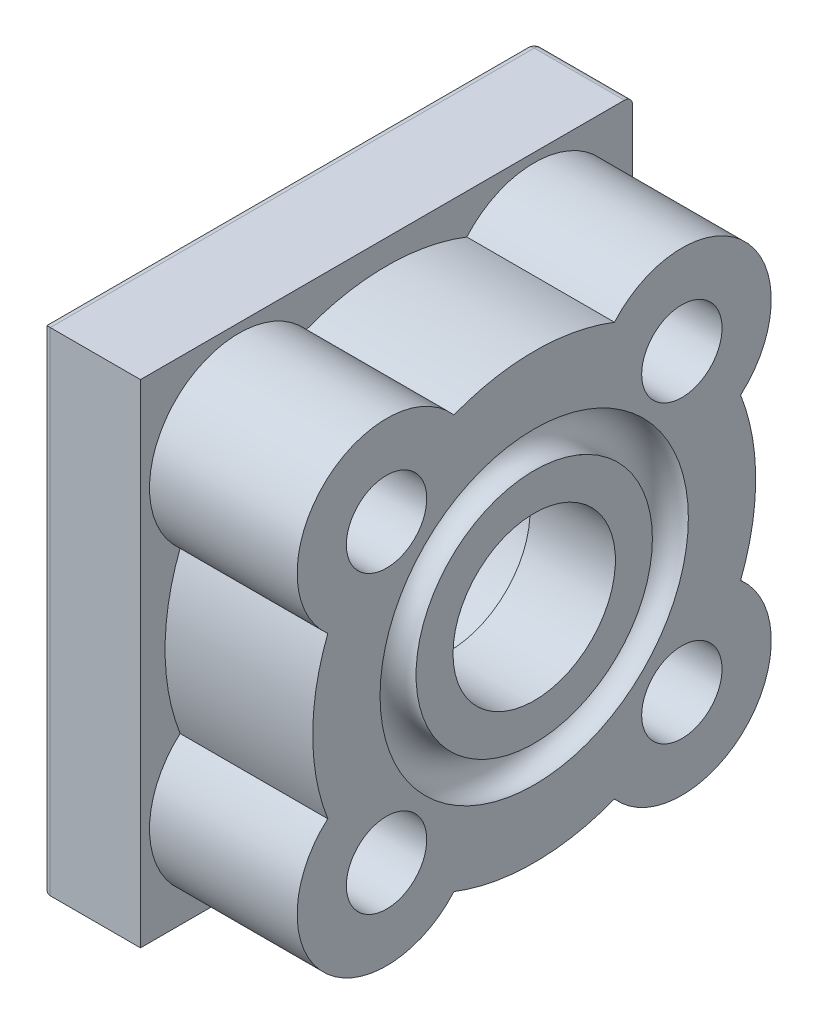
SolidWorks part; units mm, degrees
ref_plane "Front Plane" through (0, 0, 0) normal (0, 0, 1) x (1, 0, 0)
ref_plane "Top Plane" through (0, 0, 0) normal (0, 1, 0) x (1, 0, 0)
ref_plane "Right Plane" through (0, 0, 0) normal (1, 0, 0) x (0, 0, -1)
sketch "Sketch1" plane through (0, 0, 0) normal (1, 0, 0) x (0, 0, -1)
  line L1 (0, 0) -> (30, 0)
  line L2 (0, 0) -> (0, 30)
  line L3 (0, 30) -> (30, 30)
  line L4 (30, 0) -> (30, 30)
  dimension "D1" = 30
  dimension "D2" = 30
extrude "Boss-Extrude1" add sketch "Sketch1" along normal blind 15
sketch "Sketch2" plane through (0, 0, 0) normal (-1, 0, 0) x (0, 0, 1)
  line L0 (-30, 30) -> (0, 30) construction
  line L1 (-30, 0) -> (-30, 30) construction
  line L2 (0, 30) -> (0, 0) construction
  line L3 (0, 0) -> (-30, 0) construction
  circle A0 centre (-24, 24) radius 2.45
  circle A1 centre (-6, 24) radius 2.45
  circle A2 centre (-6, 6) radius 2.45
  circle A3 centre (-24, 6) radius 2.45
  dimension "D2" = 6
  dimension "D3" = 6
  dimension "D5" = 6
  dimension "D6" = 6
  dimension "D7" = 6
  dimension "D8" = 6
  dimension "D9" = 4.9
  dimension "D1" = 6
  dimension "D4" = 6
extrude "Cut-Extrude1" cut sketch "Sketch2" against normal through all
sketch "Sketch3" plane through (0, 0, 0) normal (-1, 0, 0) x (0, 0, 1)
  line L0 (-30, 30) -> (0, 30) construction
  line L1 (-7.6099, 15) -> (-11.305, 21.4)
  line L2 (-11.305, 21.4) -> (-18.695, 21.4)
  line L3 (-18.695, 21.4) -> (-22.3901, 15)
  line L4 (-22.3901, 15) -> (-18.695, 8.6)
  line L5 (-18.695, 8.6) -> (-11.305, 8.6)
  line L6 (-11.305, 8.6) -> (-7.6099, 15)
  line L7 (0, 30) -> (0, 0) construction
  circle A0 centre (-15, 15) radius 6.4 construction
  dimension "D1" = 15
  dimension "D2" = 15
  dimension "D3" = 12.8
extrude "Cut-Extrude2" cut sketch "Sketch3" against normal blind 6.5
sketch "Sketch4" plane through (6.5, 0, 0) normal (-1, 0, 0) x (0, 0, 1)
  line L0 (-11.305, 21.4) -> (-18.695, 21.4) construction
  line L1 (-18.695, 21.4) -> (-22.3901, 15) construction
  circle A0 centre (-15, 15) radius 6.4
  dimension "D1" = 12.8
extrude "Cut-Extrude3" cut sketch "Sketch4" against normal blind 3.3
sketch "Sketch5" plane through (9.8, 0, 0) normal (-1, 0, 0) x (0, 0, 1)
  circle A0 centre (-15, 15) radius 4.95
  dimension "D1" = 9.9
extrude "Cut-Extrude4" cut sketch "Sketch5" against normal through all
ref_plane "Plane1" through (0, 0, -15) normal (0, 0, 1) x (1, 0, 0)
sketch "Sketch6" plane through (0, 0, -15) normal (0, 0, 1) x (1, 0, 0)
  line L0 (9.8, 15) -> (0, 15) construction
  line L1 (9.8, 21.4) -> (9.8, 8.6) construction
  line L2 (15, 30) -> (15, 0) construction
  circle A0 centre (14.4, 23.3) radius 1.25
  dimension "D3" = 8.3
  dimension "D4" = 2.5
  dimension "D5" = 0.6
revolve "Cut-Revolve1" cut sketch "Sketch6" angle 360 about L0
fillet "Fillet1" radius 0.5 6 edges at (7.5, 0, -30) (0, 15, -30) (0, 0, -15) (0, 15, 0) (0, 30, -15) (7.5, 30, -30)
sketch "Sketch7" plane through (0, 0, 0) normal (-1, 0, 0) x (0, 0, 1)
  line L1 (-18.6306, 24) -> (-21.3153, 28.65)
  line L2 (-21.3153, 28.65) -> (-26.6847, 28.65)
  line L3 (-26.6847, 28.65) -> (-29.3694, 24)
  line L4 (-29.3694, 24) -> (-26.6847, 19.35)
  line L5 (-26.6847, 19.35) -> (-21.3153, 19.35)
  line L6 (-21.3153, 19.35) -> (-18.6306, 24)
  line L7 (-0.6306, 24) -> (-3.3153, 28.65)
  line L8 (-3.3153, 28.65) -> (-8.6847, 28.65)
  line L9 (-8.6847, 28.65) -> (-11.3694, 24)
  line L10 (-11.3694, 24) -> (-8.6847, 19.35)
  line L11 (-8.6847, 19.35) -> (-3.3153, 19.35)
  line L12 (-3.3153, 19.35) -> (-0.6306, 24)
  line L13 (-0.6306, 6) -> (-3.3153, 10.65)
  line L14 (-3.3153, 10.65) -> (-8.6847, 10.65)
  line L15 (-8.6847, 10.65) -> (-11.3694, 6)
  line L16 (-11.3694, 6) -> (-8.6847, 1.35)
  line L17 (-8.6847, 1.35) -> (-3.3153, 1.35)
  line L18 (-3.3153, 1.35) -> (-0.6306, 6)
  line L19 (-18.6306, 6) -> (-21.3153, 10.65)
  line L20 (-21.3153, 10.65) -> (-26.6847, 10.65)
  line L21 (-26.6847, 10.65) -> (-29.3694, 6)
  line L22 (-29.3694, 6) -> (-26.6847, 1.35)
  line L23 (-26.6847, 1.35) -> (-21.3153, 1.35)
  line L24 (-21.3153, 1.35) -> (-18.6306, 6)
  circle A0 centre (-24, 24) radius 4.65 construction
  circle A1 centre (-6, 24) radius 4.65 construction
  circle A2 centre (-6, 6) radius 4.65 construction
  circle A3 centre (-24, 6) radius 4.65 construction
  circle A4 centre (-24, 24) radius 2.45 construction
  circle A5 centre (-6, 24) radius 2.45 construction
  circle A6 centre (-6, 6) radius 2.45 construction
  circle A7 centre (-24, 6) radius 2.45 construction
  dimension "D1" = 9.3
extrude "Cut-Extrude5" cut sketch "Sketch7" against normal blind 3.2
sketch "Sketch9" plane through (15, 0, 0) normal (1, 0, 0) x (0, 0, -1)
  line L0 (0, 30) -> (0, 0) construction
  line L5 (-2, 32) -> (32, 32)
  line L6 (-2, 32) -> (-2, -2)
  line L7 (-2, -2) -> (32, -2)
  line L8 (32, 32) -> (32, -2)
  line L9 (29.5, 30) -> (0, 30) construction
  line L10 (30, 0.5) -> (30, 29.5) construction
  line L11 (0, 0) -> (29.5, 0) construction
  arc A0 (10.1073, 27.5822) -> (2.4178, 19.8927) centre (6, 24) ccw
  arc A1 (27.5822, 19.8927) -> (19.8927, 27.5822) centre (24, 24) ccw
  arc A2 (19.8927, 2.4178) -> (27.5822, 10.1073) centre (24, 6) ccw
  arc A3 (2.4178, 10.1073) -> (10.1073, 2.4178) centre (6, 6) ccw
  arc A4 (2.4178, 19.8927) -> (2.4178, 10.1073) centre (15, 15) ccw
  circle A5 centre (6, 24) radius 2.45 construction
  circle A6 centre (24, 24) radius 2.45 construction
  circle A7 centre (24, 6) radius 2.45 construction
  circle A8 centre (6, 6) radius 2.45 construction
  arc A9 (19.8927, 27.5822) -> (10.1073, 27.5822) centre (15, 15) ccw
  arc A10 (27.5822, 10.1073) -> (27.5822, 19.8927) centre (15, 15) ccw
  arc A11 (10.1073, 2.4178) -> (19.8927, 2.4178) centre (15, 15) ccw
  dimension "D1" = 3
  dimension "D2" = 3
  dimension "D3" = 3
  dimension "D4" = 3
  dimension "D5" = 27
  dimension "D6" = 2
  dimension "D7" = 2
  dimension "D8" = 2
  dimension "D9" = 2
extrude "Cut-Extrude7" cut sketch "Sketch9" against normal blind 9
